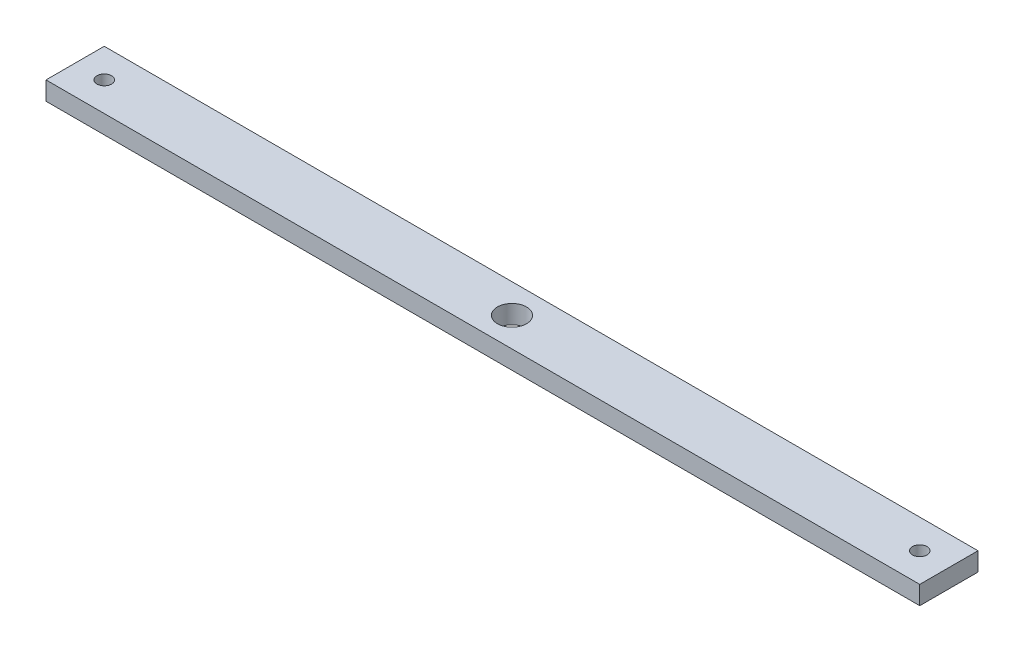
SolidWorks part; units mm, degrees
ref_plane "Front Plane" through (0, 0, 0) normal (0, 0, 1) x (1, 0, 0)
ref_plane "Top Plane" through (0, 0, 0) normal (0, 1, 0) x (1, 0, 0)
ref_plane "Right Plane" through (0, 0, 0) normal (1, 0, 0) x (0, 0, -1)
sketch "Sketch1" plane through (0, 0, 0) normal (0, 1, 0) x (1, 0, 0)
  line L0 (-150, 0) -> (-140, 0) construction
  line L1 (-150, -10) -> (150, -10)
  line L2 (-150, -10) -> (-150, 10)
  line L3 (-150, 10) -> (150, 10)
  line L4 (150, -10) -> (150, 10)
  line L5 (-150, -10) -> (150, 10) construction
  line L6 (-150, 10) -> (150, -10) construction
  line L7 (-140, 0) -> (-140, -10) construction
  line L8 (150, 0) -> (140, 0) construction
  circle A0 centre (0, 0) radius 5
  circle A1 centre (-140, 0) radius 2.5
  circle A2 centre (140, 0) radius 2.5
  point P0 (0, 0)
  dimension "D3" = 5
  dimension "D4" = 10
  dimension "D1" = 300
  dimension "D2" = 20
extrude "Boss-Extrude1" add sketch "Sketch1" along normal mid plane 6.35
